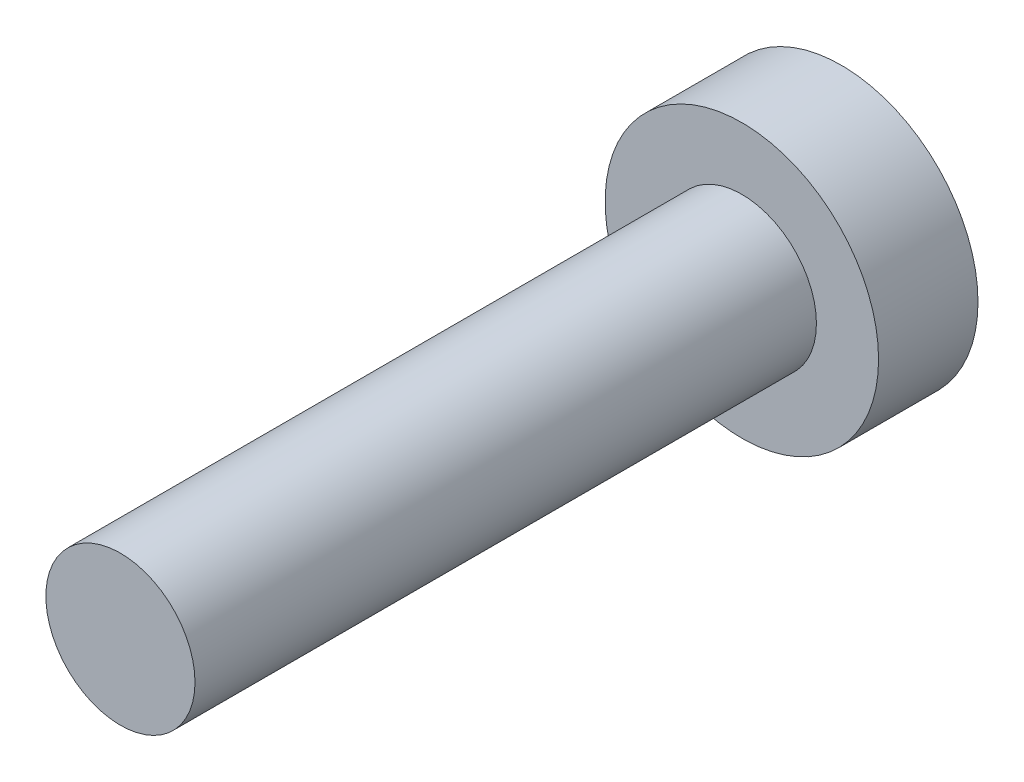
SolidWorks part; units mm, degrees
other "Rear Spring Shoulder Bolt"
ref_plane "Front Plane" through (0, 0, 0) normal (0, 0, 1) x (1, 0, 0)
ref_plane "Top Plane" through (0, 0, 0) normal (0, 1, 0) x (1, 0, 0)
ref_plane "Right Plane" through (0, 0, 0) normal (1, 0, 0) x (0, 0, -1)
sketch3d "Smooth eyelet shoulder sketch datum points"
  point P0 (35.7083, -12, 9)
  point P1 (45.7083, -12, 9)
  point P2 (35.7083, -2, 9)
ref_plane "Smooth eyelet shoulder sketch plane" through (0, 0, 9) normal (0, 0, 1) x (1, 0, 0)
sketch "Smooth eyelet shoulder sketch" plane through (0, 0, 9) normal (0, 0, 1) x (1, 0, 0)
  circle A0 centre (35.7083, -12) radius 1.5
extrude "Smooth eyelet shoulder" add sketch "Smooth eyelet shoulder sketch" along normal blind 12.5 separate body
sketch3d "Pin head sketch datum points"
  point P0 (35.7083, -12, 7)
  point P1 (45.7083, -12, 7)
  point P2 (35.7083, -2, 7)
ref_plane "Pin head sketch plane" through (0, 0, 7) normal (0, 0, 1) x (1, 0, 0)
sketch "Pin head sketch" plane through (0, 0, 7) normal (0, 0, 1) x (1, 0, 0)
  circle A0 centre (35.7083, -12) radius 2.75
extrude "Pin head" add sketch "Pin head sketch" along normal blind 2
